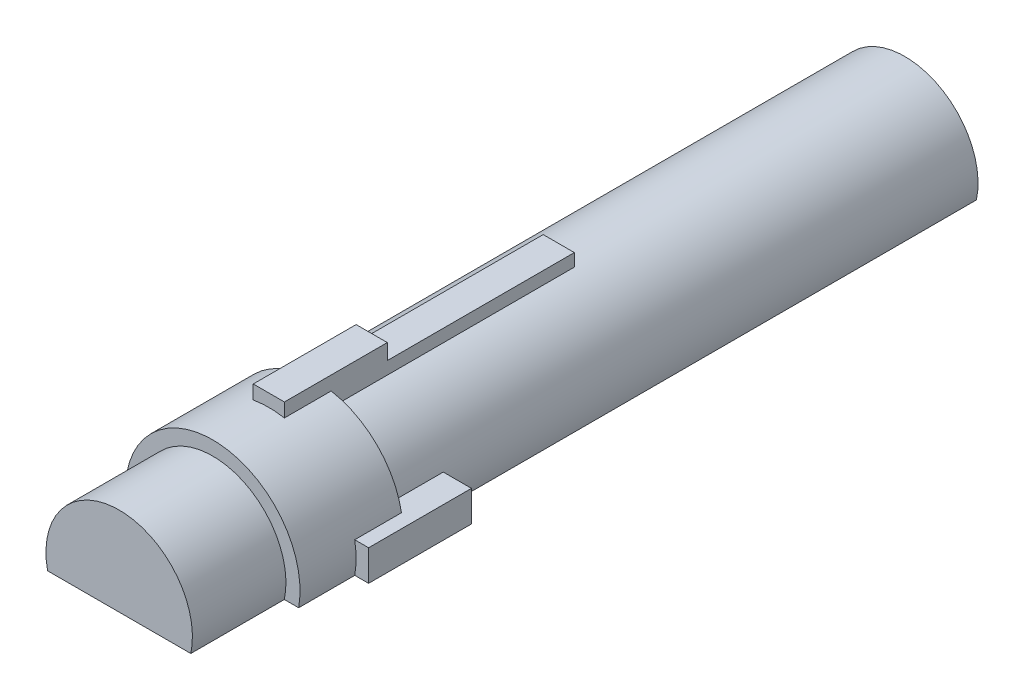
SolidWorks part; units mm, degrees
ref_plane "Front Plane" through (0, 0, 0) normal (0, 0, 1) x (1, 0, 0)
ref_plane "Top Plane" through (0, 0, 0) normal (0, 1, 0) x (1, 0, 0)
ref_plane "Right Plane" through (0, 0, 0) normal (1, 0, 0) x (0, 0, -1)
sketch "Sketch1" plane through (0, 0, 0) normal (0, 0, 1) x (1, 0, 0)
  line L4 (3.8291, -0.8156) -> (-3.8291, -0.8156)
  arc A0 (3.915, 0) -> (-3.915, 0) centre (0, 0) ccw construction
  arc A1 (3.8291, -0.8156) -> (-3.8291, -0.8156) centre (0, 0) ccw
  point P6 (0, 0)
  dimension "D1" = 7.83
extrude "Boss-Extrude1" add sketch "Sketch1" along normal blind 42
sketch "Sketch2" plane through (0, 0, 42) normal (0, 0, 1) x (1, 0, 0)
  line L3 (4.5948, -0.8156) -> (-4.5948, -0.8156)
  arc A0 (4.6667, 0) -> (-4.6667, 0) centre (0, 0) ccw
  arc A1 (-4.6667, 0) -> (-4.5948, -0.8156) centre (0, 0) ccw
  arc A2 (4.5948, -0.8156) -> (4.6667, 0) centre (0, 0) ccw
  point P5 (0, 0)
  point P11 (0, -0.8156)
  dimension "D1" = 9.3333
extrude "Boss-Extrude2" add sketch "Sketch2" against normal blind 5.5 from offset 5 offset against normal yes
sketch "Sketch5" plane through (0, 0, 31.5) normal (0, 0, 1) x (1, 0, 0)
  line L1 (5.3333, 0.8333) -> (3.8253, 0.8333)
  line L2 (5.3333, 0.8333) -> (5.3333, -0.8156)
  line L4 (-5.3333, 0.8333) -> (-5.3333, -0.8156)
  line L6 (-3.8253, 0.8333) -> (-5.3333, 0.8333)
  line L7 (-0.8333, 5.3333) -> (0.8333, 5.3333)
  line L8 (-0.8333, 5.3333) -> (-0.8333, 3.8253)
  line L10 (0.8333, 5.3333) -> (0.8333, 3.8253)
  line L11 (5.3333, -0.8156) -> (-5.3333, -0.8156)
  arc A3 (-3.8253, 0.8333) -> (-0.8333, 3.8253) centre (0, 0) cw
  arc A5 (0.8333, 3.8253) -> (3.8253, 0.8333) centre (0, 0) cw
  point P11 (0, -0.8156)
  dimension "D2" = 10.6667
  dimension "D4" = 1.6667
extrude "Boss-Extrude4" add sketch "Sketch5" along normal blind 2.5 and the other way blind 3
sketch "Sketch6" plane through (0, 0, 28.5) normal (0, 0, -1) x (-1, 0, 0)
  line L0 (-0.8333, 0.2639) -> (0.8333, 0.2639)
  line L2 (0.8333, 0.2639) -> (0.8333, 4.5)
  line L3 (0.8333, 4.5) -> (-0.8333, 4.5)
  line L4 (-0.8333, 0.2639) -> (-0.8333, 4.5)
  line L6 (0.8333, 4.5) -> (0.0489, 0.2639) construction
  line L7 (-0.0489, 0.2639) -> (-0.8333, 4.5) construction
  line L8 (0, 0) -> (-0.8333, -4.5) construction
  point P0 (0, 0)
  dimension "D2" = 1.6667
extrude "Boss-Extrude5" add sketch "Sketch6" along normal blind 10
